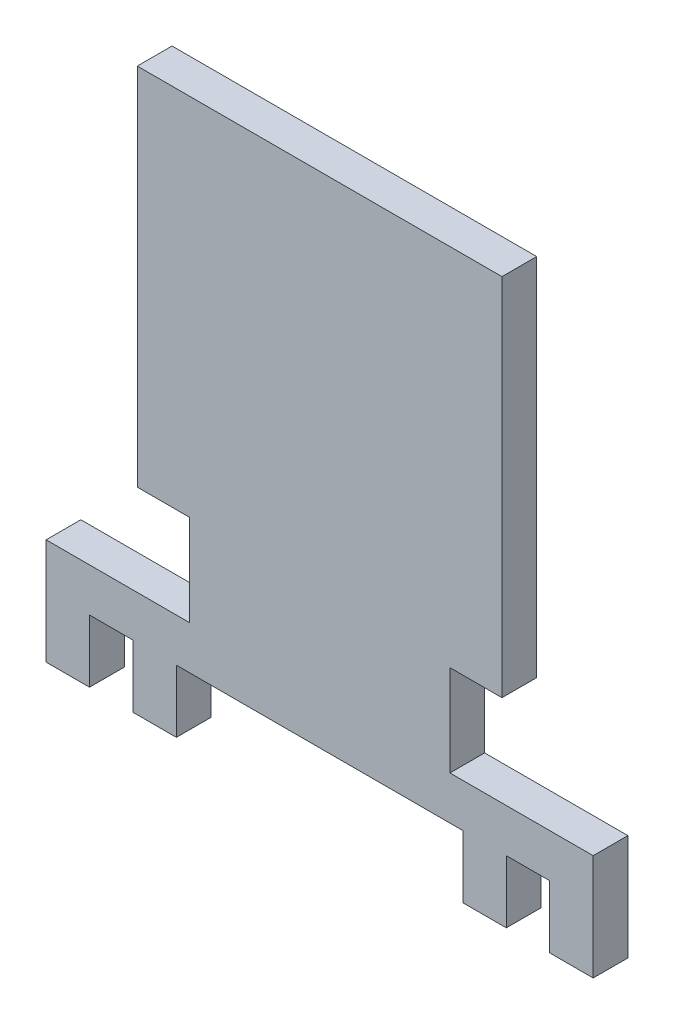
SolidWorks part; units mm, degrees
ref_plane "Front Plane" through (0, 0, 0) normal (0, 0, 1) x (1, 0, 0)
ref_plane "Top Plane" through (0, 0, 0) normal (0, 1, 0) x (1, 0, 0)
ref_plane "Right Plane" through (0, 0, 0) normal (1, 0, 0) x (0, 0, -1)
sketch "Sketch1" plane through (0, 0, 0) normal (0, 0, 1) x (1, 0, 0)
  line L0 (-67.3369, 30.4418) -> (-29.2369, 30.4418)
  line L1 (-29.2369, 30.4418) -> (-29.2369, -9.5582)
  line L2 (-29.2369, -9.5582) -> (-8.287, -9.5582)
  line L3 (-8.287, -9.5582) -> (-8.287, -15.9082)
  line L4 (-8.287, -15.9082) -> (-88.2869, -15.9082)
  line L5 (-88.2869, -15.9082) -> (-88.2869, -9.5582)
  line L6 (-88.2869, -9.5582) -> (-67.3369, -9.5582)
  line L7 (-67.3369, -9.5582) -> (-67.3369, 30.4418)
  dimension "D1" = 40
  dimension "D2" = 38.1
  dimension "D3" = 20.9499
  dimension "D4" = 20.9499
  dimension "D5" = 6.35
extrude "Boss-Extrude1" add sketch "Sketch1" along normal blind 5.08
sketch "Sketch2" plane through (0, 0, 0) normal (0, 0, -1) x (-1, 0, 0)
  line L0 (88.2869, -15.9082) -> (8.287, -15.9082) construction
  line L2 (88.2869, -15.9082) -> (81.9369, -15.9082)
  line L3 (88.2869, -15.9082) -> (88.2869, -25.0522)
  line L4 (88.2869, -25.0522) -> (81.9369, -25.0522)
  line L5 (75.5869, -15.9082) -> (69.2369, -15.9082)
  line L6 (75.5869, -15.9082) -> (75.5869, -25.0522)
  line L7 (75.5869, -25.0522) -> (69.2369, -25.0522)
  line L8 (69.2369, -15.9082) -> (69.2369, -25.0522)
  line L9 (81.9369, -15.9082) -> (81.9369, -25.0522)
  line L10 (8.287, -15.9082) -> (14.637, -15.9082)
  line L11 (8.287, -15.9082) -> (8.287, -25.0522)
  line L12 (8.287, -25.0522) -> (14.637, -25.0522)
  line L13 (14.637, -15.9082) -> (14.637, -25.0522)
  line L14 (20.987, -15.9082) -> (27.337, -15.9082)
  line L15 (20.987, -15.9082) -> (20.987, -25.0522)
  line L16 (20.987, -25.0522) -> (27.337, -25.0522)
  line L17 (27.337, -15.9082) -> (27.337, -25.0522)
  line L18 (62.8869, -15.9082) -> (56.5369, -15.9082)
  line L19 (62.8869, -15.9082) -> (62.8869, -25.0522)
  line L20 (62.8869, -25.0522) -> (56.5369, -25.0522)
  line L21 (56.5369, -15.9082) -> (56.5369, -25.0522)
  line L22 (40.037, -15.9082) -> (33.687, -15.9082)
  line L23 (40.037, -15.9082) -> (40.037, -25.0522)
  line L24 (40.037, -25.0522) -> (33.687, -25.0522)
  line L25 (33.687, -15.9082) -> (33.687, -25.0522)
  dimension "D1" = 6.35
  dimension "D2" = 6.35
  dimension "D3" = 6.35
  dimension "D4" = 6.35
  dimension "D5" = 9.144
  dimension "D6" = 9.144
  dimension "D7" = 6.35
  dimension "D8" = 6.35
  dimension "D9" = 9.144
  dimension "D10" = 9.144
  dimension "D11" = 6.35
  dimension "D12" = 9.144
  dimension "D13" = 9.144
  dimension "D14" = 6.35
  dimension "D15" = 6.35
  dimension "D16" = 6.35
extrude "Boss-Extrude2" add sketch "Sketch2" against normal blind 5.08
sketch "Sketch3" plane through (0, 0, 0) normal (0, 0, -1) x (-1, 0, 0)
  line L0 (48.2869, 30.4418) -> (48.2869, -15.9082) construction
  line L1 (29.2369, 30.4418) -> (67.3369, 30.4418) construction
  line L2 (56.5369, -15.9082) -> (40.037, -15.9082) construction
  line L4 (74.9519, 57.1068) -> (21.6219, 57.1068)
  line L5 (74.9519, 57.1068) -> (74.9519, 3.7768)
  line L6 (74.9519, 3.7768) -> (21.6219, 3.7768)
  line L7 (21.6219, 57.1068) -> (21.6219, 3.7768)
  line L8 (74.9519, 57.1068) -> (21.6219, 3.7768) construction
  line L9 (74.9519, 3.7768) -> (21.6219, 57.1068) construction
  dimension "D1" = 53.33
  dimension "D2" = 53.33
extrude "markerBack" add sketch "Sketch3" against normal blind 5.08
sketch "Sketch4" plane through (0, 0, 5.08) normal (0, 0, 1) x (1, 0, 0)
  line L1 (-62.8869, -15.9082) -> (-33.687, -15.9082)
  line L2 (-62.8869, -15.9082) -> (-62.8869, -25.0522)
  line L3 (-62.8869, -25.0522) -> (-33.687, -25.0522)
  line L4 (-33.687, -15.9082) -> (-33.687, -25.0522)
extrude "Cut-Extrude1" cut sketch "Sketch4" against normal blind 5.08
